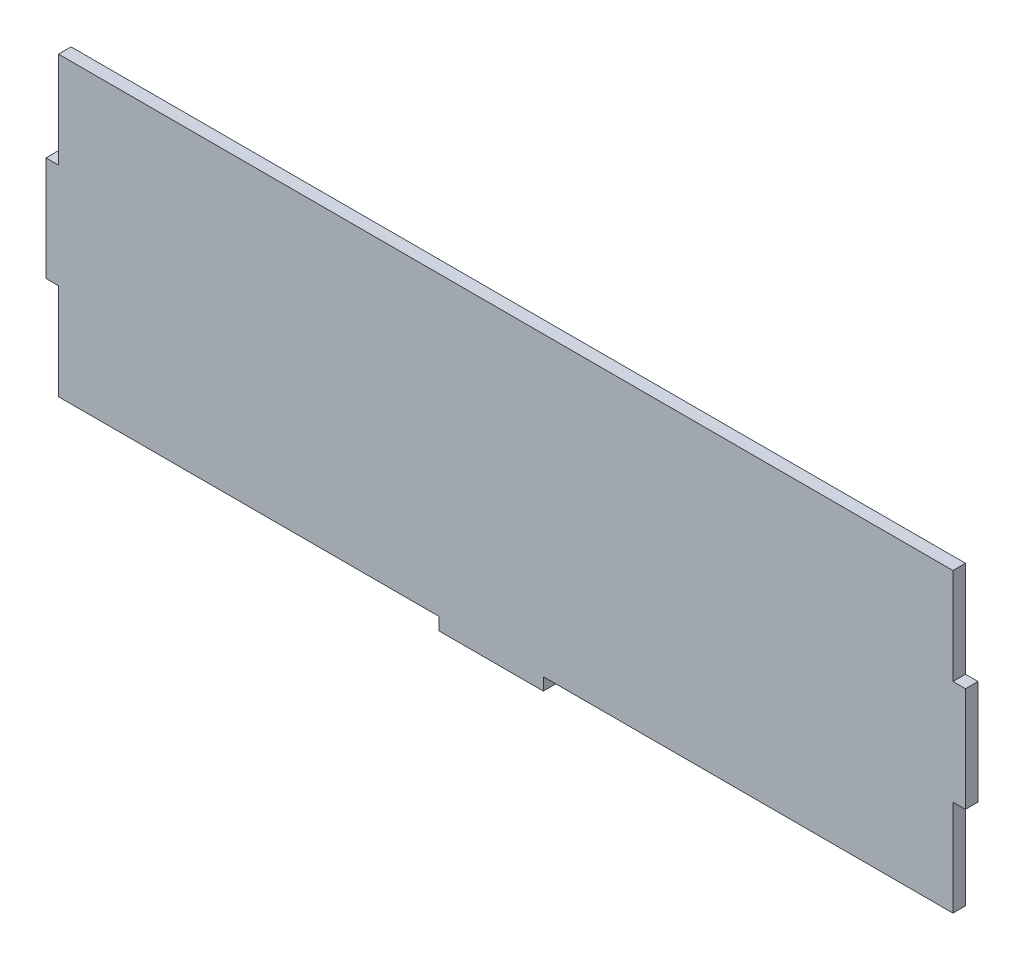
SolidWorks part; units mm, degrees
material "Maple"
ref_plane "Front Plane" through (0, 0, 0) normal (0, 0, 1) x (1, 0, 0)
ref_plane "Top Plane" through (0, 0, 0) normal (0, 1, 0) x (1, 0, 0)
ref_plane "Right Plane" through (0, 0, 0) normal (1, 0, 0) x (0, 0, -1)
sketch "Sketch1" plane through (0, 0, 0) normal (0, 0, 1) x (1, 0, 0)
  line L0 (214, 0) -> (214, -45) construction
  line L1 (0, 0) -> (428, 0)
  line L2 (0, 0) -> (0, -46)
  line L4 (428, 0) -> (428, -46)
  line L5 (546, -45) -> (214, -45) construction
  line L16 (0, -96) -> (0, -142)
  line L17 (-6, -46) -> (0, -46)
  line L22 (-6, -46) -> (-6, -96)
  line L23 (-6, -96) -> (0, -96)
  line L27 (434, -96) -> (428, -96)
  line L28 (434, -46) -> (434, -96)
  line L29 (434, -46) -> (428, -46)
  line L30 (428, -96) -> (428, -142)
  line L43 (428, -142) -> (232, -142)
  line L44 (182, -142) -> (0, -142)
  line L46 (182, -142) -> (182, -148)
  line L47 (182, -148) -> (232, -148)
  line L48 (232, -142) -> (232, -148)
  point P10 (9, -45)
  point P13 (214, -90)
  dimension "D1" = 428
  dimension "D2" = 142
  dimension "D3" = 50
  dimension "D4" = 50
  dimension "D5" = 182
  dimension "D6" = 46
  dimension "D7" = 6
  dimension "D8" = 6
  dimension "D9" = 6
  dimension "D10" = 50
  dimension "D11" = 46
extrude "Boss-Extrude1" add sketch "Sketch1" along normal blind 6
